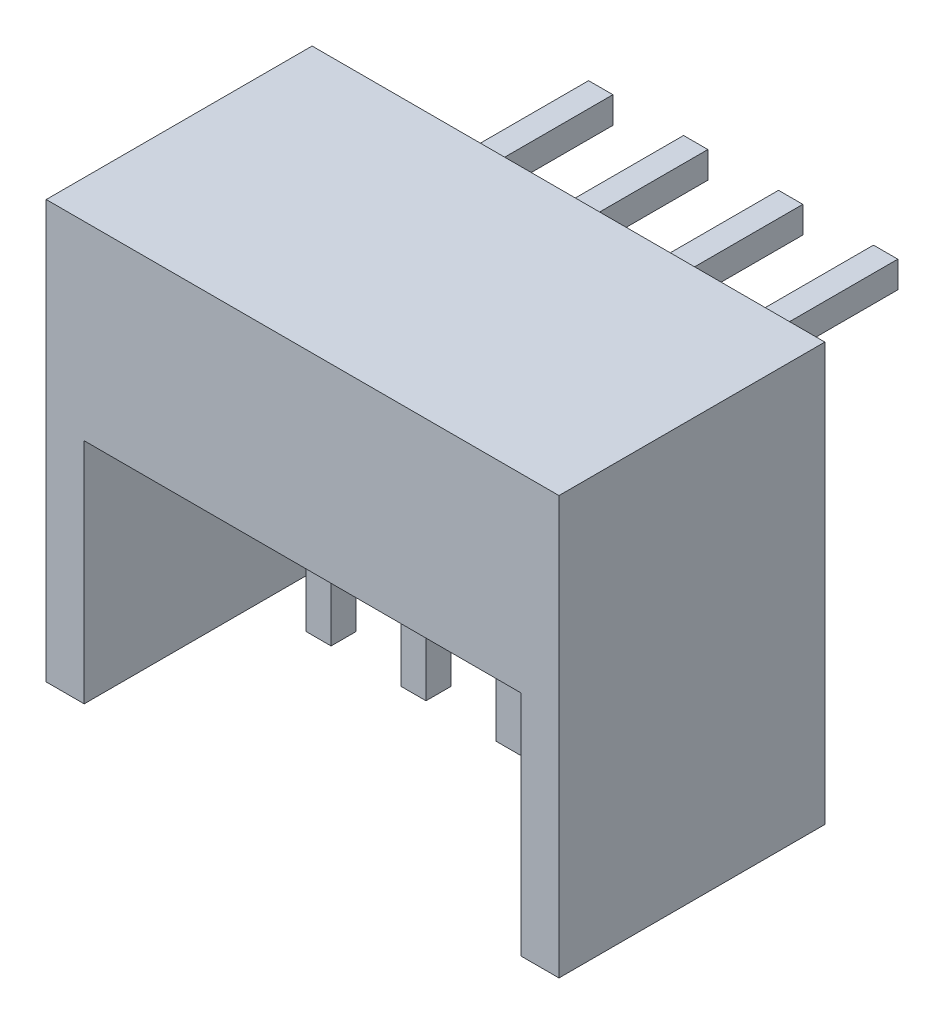
SolidWorks part; units mm, degrees
ref_plane "Спереди" through (0, 0, 0) normal (0, 0, 1) x (1, 0, 0)
ref_plane "Сверху" through (0, 0, 0) normal (0, 1, 0) x (1, 0, 0)
ref_plane "Справа" through (0, 0, 0) normal (1, 0, 0) x (0, 0, -1)
sketch "Эскиз1" plane through (0, 0, 0) normal (0, 0, 1) x (1, 0, 0)
  line L1 (-3.375, 0) -> (3.375, 0)
  line L2 (-3.375, 0) -> (-3.375, 5.5)
  line L3 (-3.375, 5.5) -> (3.375, 5.5)
  line L4 (3.375, 0) -> (3.375, 5.5)
  dimension "D1" = 6.75
  dimension "D2" = 5.5
extrude "Бобышка-Вытянуть1" add sketch "Эскиз1" along normal blind 3.5
sketch "Эскиз2" plane through (0, 0, 0) normal (0, 0, -1) x (-1, 0, 0)
  line L1 (-0.785, 4.625) -> (-0.465, 4.625)
  line L2 (-0.785, 4.625) -> (-0.785, 4.275)
  line L3 (-0.785, 4.275) -> (-0.465, 4.275)
  line L4 (-0.465, 4.625) -> (-0.465, 4.275)
  line L5 (-0.785, 4.625) -> (-0.465, 4.275) construction
  line L6 (-0.785, 4.275) -> (-0.465, 4.625) construction
  point P0 (-0.625, 4.45)
  point P20 (0, 0)
  dimension "D1" = 4.45
  dimension "D2" = 0.625
  dimension "D3" = 0.32
  dimension "D4" = 0.35
extrude "Бобышка-Вытянуть2" add sketch "Эскиз2" along normal blind 2.3
sketch "Эскиз3" plane through (0, 0, 0) normal (0, -1, 0) x (1, 0, 0)
  line L0 (3.375, 3.5) -> (3.375, 0) construction
  line L1 (2.875, 3.5) -> (-2.875, 3.5)
  line L2 (2.875, 3.5) -> (2.875, 0.5)
  line L3 (2.875, 0.5) -> (-2.875, 0.5)
  line L4 (-2.875, 3.5) -> (-2.875, 0.5)
  line L5 (2.875, 3.5) -> (-2.875, 0.5) construction
  line L6 (2.875, 0.5) -> (-2.875, 3.5) construction
  line L8 (-3.375, 0) -> (3.375, 0) construction
  line L9 (-3.375, 3.5) -> (3.375, 3.5) construction
  point P0 (0, 2)
  point P5 (0, 0)
  dimension "D1" = 0.5
  dimension "D2" = 0.5
  dimension "D3" = 0
extrude "Вырез-Вытянуть1" cut sketch "Эскиз3" against normal blind 3
sketch "Эскиз4" plane through (0, 3, 0) normal (0, -1, 0) x (1, 0, 0)
  line L0 (-2.875, 0.5) -> (2.875, 0.5) construction
  line L1 (0.79, 1.415) -> (0.46, 1.415)
  line L2 (0.79, 1.415) -> (0.79, 1.085)
  line L3 (0.79, 1.085) -> (0.46, 1.085)
  line L4 (0.46, 1.415) -> (0.46, 1.085)
  line L5 (0.79, 1.415) -> (0.46, 1.085) construction
  line L6 (0.79, 1.085) -> (0.46, 1.415) construction
  point P0 (0.625, 1.25)
  point P5 (0, 0)
  dimension "D1" = 0.33
  dimension "D2" = 0.33
  dimension "D3" = 0.75
extrude "Бобышка-Вытянуть3" add sketch "Эскиз4" along normal blind 2.8
pattern_linear "Линейный массив3" count 2 spacing 1.25 along (1, 0, 0) count 3 spacing 1.25 along (-1, 0, 0) of "Бобышка-Вытянуть2", "Бобышка-Вытянуть3"
